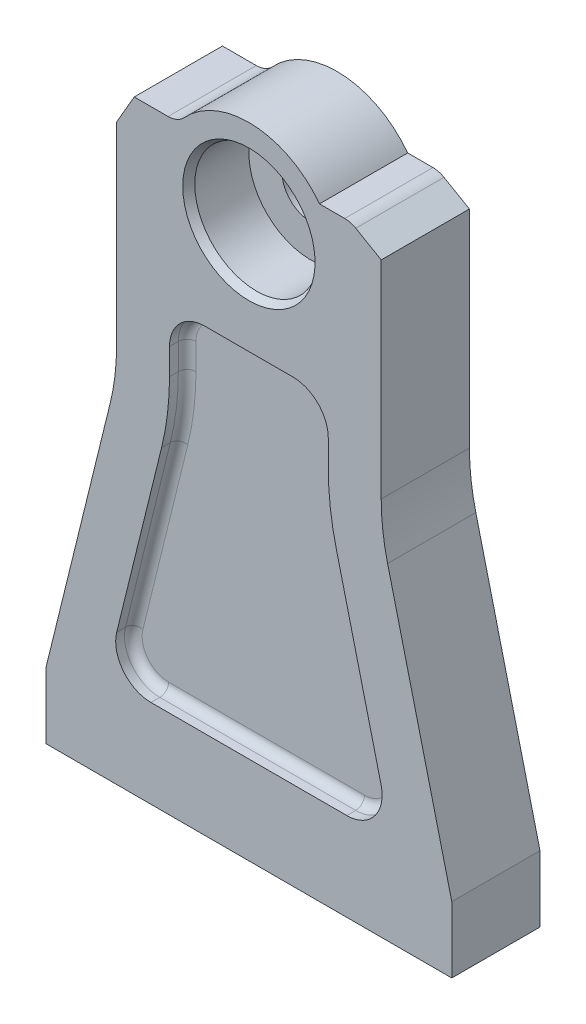
SolidWorks part; units mm, degrees
ref_plane "Front Plane" through (0, 0, 0) normal (0, 0, 1) x (1, 0, 0)
ref_plane "Top Plane" through (0, 0, 0) normal (0, 1, 0) x (1, 0, 0)
ref_plane "Right Plane" through (0, 0, 0) normal (1, 0, 0) x (0, 0, -1)
sketch "Sketch1" plane through (0, 0, 0) normal (0, 0, 1) x (1, 0, 0)
  line L0 (-46, 0) -> (46, 0)
  line L1 (46, 0) -> (46, 15)
  line L2 (46, 15) -> (31.4493, 74.1124)
  line L3 (30, 86.0633) -> (30, 137)
  line L4 (30, 137) -> (16, 137)
  line L5 (0, 167.6734) -> (0, -62.9922) construction
  line L6 (-46, 0) -> (-46, 15)
  line L7 (-46, 15) -> (-31.4493, 74.1124)
  line L8 (-30, 86.0633) -> (-30, 137)
  line L9 (-30, 137) -> (-16, 137)
  arc A0 (16, 137) -> (-16, 137) centre (0, 125) ccw
  circle A1 centre (0, 125) radius 6.5
  arc A2 (31.4493, 74.1124) -> (30, 86.0633) centre (80, 86.0633) cw
  arc A3 (-31.4493, 74.1124) -> (-30, 86.0633) centre (-80, 86.0633) ccw
  point P13 (0, 0)
  point P18 (30, 80)
  point P21 (-30, 80)
  dimension "D1" = 40
  dimension "D2" = 13
  dimension "D9" = 50
  dimension "D3" = 125
  dimension "D4" = 46
  dimension "D5" = 15
  dimension "D6" = 65
  dimension "D7" = 30
  dimension "D8" = 12
extrude "Boss-Extrude1" add sketch "Sketch1" along normal mid plane 20
sketch "Sketch2" plane through (0, 0, 10) normal (0, 0, 1) x (1, 0, 0)
  circle A0 centre (0, 125) radius 14
  dimension "D1" = 28
extrude "Cut-Extrude1" cut sketch "Sketch2" against normal blind 14
chamfer "Chamfer1" distance 1 angle 60 1 edges at (14, 125, 10)
chamfer "Chamfer2" distance 4 angle 60 2 edges at (-30, 137, 0) (30, 137, 0)
fillet "Fillet1" radius 5 2 edges at (-16, 137, 0) (23.0718, 137, 0)
sketch "Sketch4" plane through (0, 0, 10) normal (0, 0, 1) x (1, 0, 0)
  line L0 (-10, 100) -> (10, 100)
  line L72 (18, 86.0633) -> (18, 133)
  line L73 (34.3478, 12.1318) -> (19.7971, 71.2442)
  line L74 (18, 86.0633) -> (18, 92)
  line L75 (29.9711, 29.9122) -> (19.7971, 71.2442)
  line L80 (-18, 130.0718) -> (-18, 86.0633)
  line L81 (-18, 92) -> (-18, 86.0633)
  line L85 (-22.203, 20) -> (22.203, 20)
  line L86 (-46, 0) -> (46, 0) construction
  line L87 (-19.7971, 71.2442) -> (-34.3478, 12.1318)
  line L88 (-18, 130.0718) -> (-18, 86.0633)
  line L89 (-19.7971, 71.2442) -> (-29.9711, 29.9122)
  line L90 (-18, 100) -> (-18, 86.0633)
  arc A0 (22.203, 20) -> (29.9711, 29.9122) centre (22.203, 28) ccw
  arc A1 (-22.203, 20) -> (-29.9711, 29.9122) centre (-22.203, 28) cw
  arc A4 (10, 100) -> (18, 92) centre (10, 92) cw
  arc A5 (-10, 100) -> (-18, 92) centre (-10, 92) ccw
  arc A37 (18, 86.0633) -> (19.7971, 71.2442) centre (80, 86.0633) ccw
  arc A38 (18, 86.0633) -> (19.7971, 71.2442) centre (80, 86.0633) ccw
  arc A43 (-19.7971, 71.2442) -> (-18, 86.0633) centre (-80, 86.0633) ccw
  arc A44 (-19.7971, 71.2442) -> (-18, 86.0633) centre (-80, 86.0633) ccw
  point P12 (0, 0)
  dimension "D6" = 8
  dimension "D7" = 8
  dimension "D4" = 20
  dimension "D5" = 80
  dimension "D1" = 12
  dimension "D2" = 12
  dimension "D3" = 12
extrude "Cut-Extrude2" cut sketch "Sketch4" against normal blind 4 contours A44 L89 A1 L85 A0 L75 A38 L74 A4 L0 A5 L81
fillet "Fillet2" radius 2 12 edges at (-18, 89.0317, 6) (-15.6569, 97.6569, 6) (0, 100, 6) (15.6569, 97.6569, 6) (18, 89.0317, 6) (18.4509, 78.5995, 6) (24.8841, 50.5782, 6) (28.4997, 23.0653, 6) (0, 20, 6) (-28.4997, 23.0653, 6) (-24.8841, 50.5782, 6) (-18.4509, 78.5995, 6)
mirror "Mirror1" about plane through (0, 0, 0) normal (0, 0, 1) of "Cut-Extrude2", "Fillet2"
hole_wizard "M10x1.25 Tapped Hole1" positions "Sketch5" profile "Sketch6" tap size "M10x1.25" standard "ISO"
sketch "Sketch5" plane through (0, 0, 0) normal (0, -1, 0) x (-1, 0, 0)
  line L0 (-46, -10) -> (-46, 10) construction
  point P0 (-30, 0)
  point P2 (30, 0)
  point P7 (-46, 0)
  point P9 (0, 0)
  dimension "D1" = 60
  dimension "D2" = 16
  dimension "D3" = 10
sketch "Sketch6" plane through (30, 0, 0) normal (1, 0, 0) x (0, 0, -1)
  line L0 (0, 0) -> (0, 22.6438)
  line L1 (0, 22.6438) -> (4.4, 20)
  line L2 (4.4, 20) -> (4.4, 0)
  line L5 (4.4, 0) -> (0, 0)
  line L10 (0, 22.6438) -> (-4.4, 20) construction
  line L11 (0, -6.35) -> (0, 107.95) construction
  dimension "Tap Drill Dia." = 8.8
  dimension "Tap Drill Depth" = 20
  dimension "Drill Angle" = 118
cosmetic thread "Hole Thread1" parameters "D1"=20, "D2"=10
cosmetic thread "Hole Thread2" parameters "D1"=20, "D2"=10
